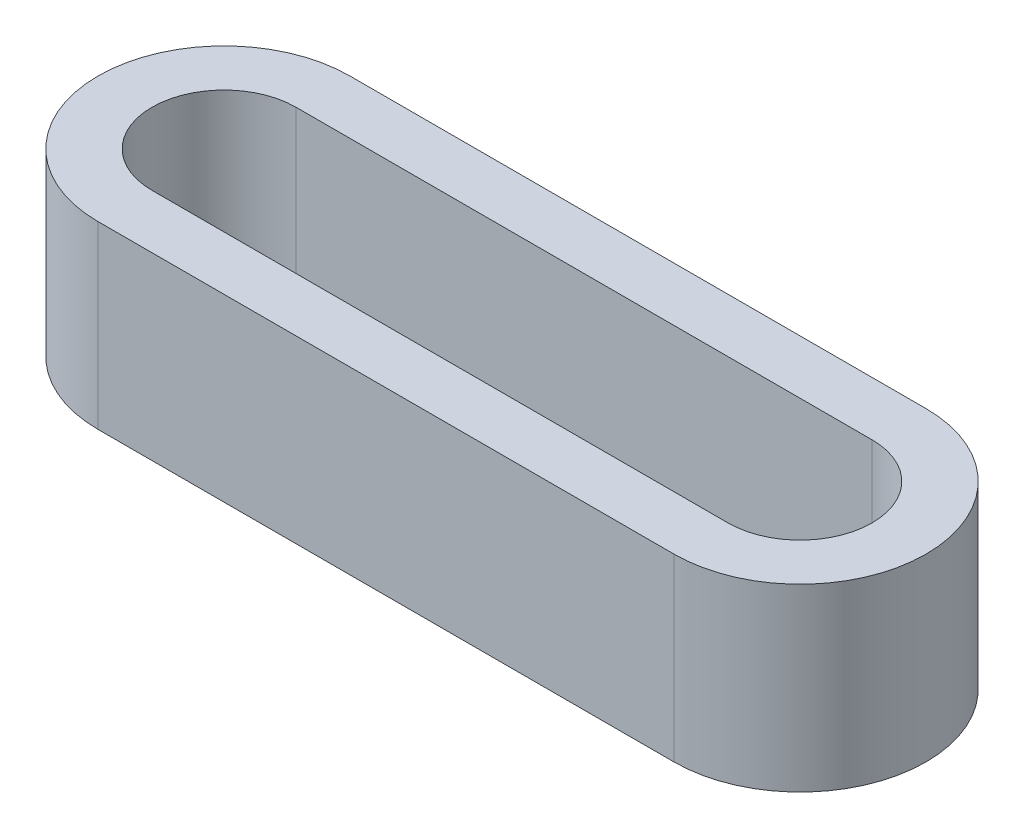
SolidWorks part; units mm, degrees
ref_plane "Płaszczyzna przednia" through (0, 0, 0) normal (0, 0, 1) x (1, 0, 0)
ref_plane "Płaszczyzna górna" through (0, 0, 0) normal (0, 1, 0) x (1, 0, 0)
ref_plane "Płaszczyzna prawa" through (0, 0, 0) normal (1, 0, 0) x (0, 0, -1)
sketch "Szkic2" plane through (0, 0, 0) normal (0, 1, 0) x (1, 0, 0)
  line L0 (0, 0) -> (32, 0) construction
  line L1 (0, 4) -> (32, 4)
  line L2 (0, -4) -> (32, -4)
  line L3 (0, 0) -> (32, 0) construction
  line L4 (0, 7) -> (32, 7)
  line L5 (0, -7) -> (32, -7)
  line L6 (0, 7) -> (0, 4) construction
  arc A0 (0, 4) -> (0, -4) centre (0, 0) ccw
  arc A1 (32, -4) -> (32, 4) centre (32, 0) ccw
  arc A2 (0, 7) -> (0, -7) centre (0, 0) ccw
  arc A3 (32, -7) -> (32, 7) centre (32, 0) ccw
  point P3 (16, 0)
  point P10 (16, 0)
  dimension "D2" = 4
  dimension "D1" = 32
  dimension "D3" = 3
extrude "Dodanie-wyciągnięcie1" add sketch "Szkic2" along normal blind 10
